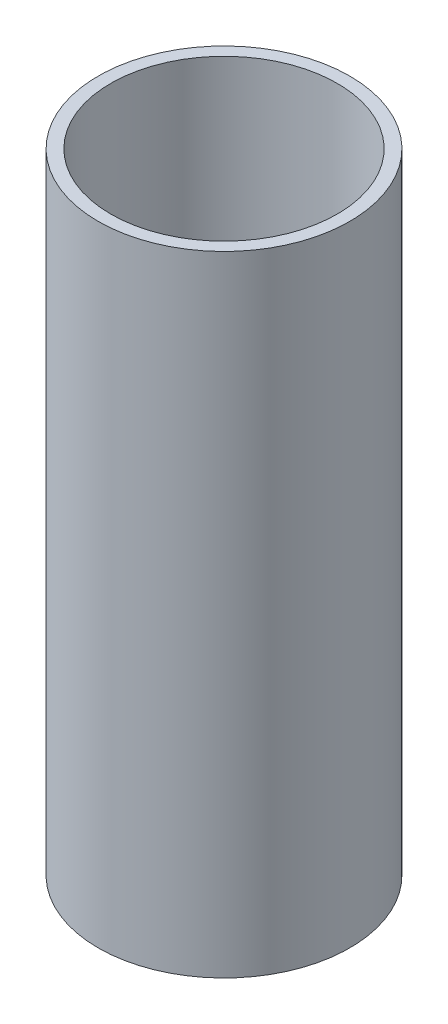
SolidWorks part; units mm, degrees
ref_plane "前视基准面" through (0, 0, 0) normal (0, 0, 1) x (1, 0, 0)
ref_plane "上视基准面" through (0, 0, 0) normal (0, 1, 0) x (1, 0, 0)
ref_plane "右视基准面" through (0, 0, 0) normal (1, 0, 0) x (0, 0, -1)
other "Configuration Table"
sketch "草图1" plane through (0, 0, 0) normal (0, 1, 0) x (1, 0, 0)
  circle A0 centre (0, 0) radius 20
  circle A1 centre (0, 0) radius 18
  dimension "D1" = 40
  dimension "D2" = 36
extrude "凸台-拉伸1" add sketch "草图1" along normal blind 100
